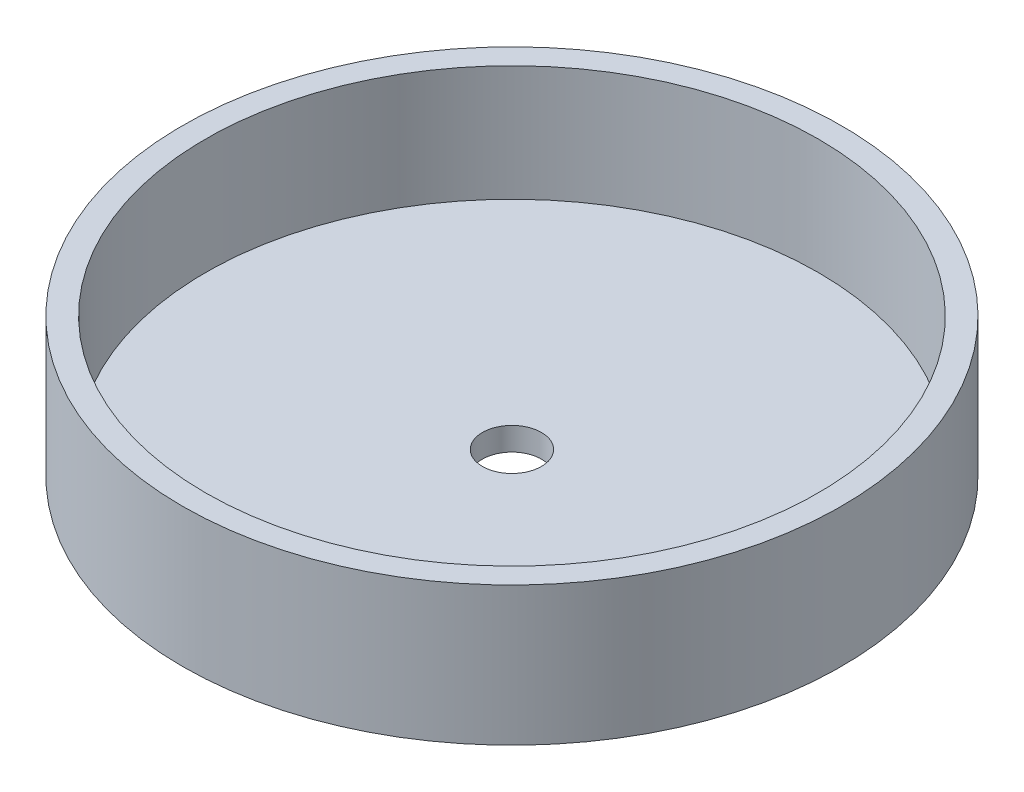
SolidWorks part; units mm, degrees
ref_plane "前视基准面" through (0, 0, 0) normal (0, 0, 1) x (1, 0, 0)
ref_plane "上视基准面" through (0, 0, 0) normal (0, 1, 0) x (1, 0, 0)
ref_plane "右视基准面" through (0, 0, 0) normal (1, 0, 0) x (0, 0, -1)
sketch "草图1" plane through (0, 0, 0) normal (0, 0, 1) x (1, 0, 0)
  line L0 (0, 9.9462) -> (0, -6.3172) construction
  line L1 (0, -3) -> (2.55, -3) construction
  line L2 (8.5753, 0) -> (-12.3118, 0) construction
  line L3 (2.55, -3) -> (2.55, 0) construction
  line L4 (2.55, 0) -> (26.5, 0)
  line L5 (26.5, 0) -> (26.5, 10)
  line L6 (26.5, 10) -> (0, 10) construction
  line L8 (0, -5) -> (4.55, -5) construction
  line L9 (4.55, -5) -> (4.55, -2) construction
  line L10 (4.55, -2) -> (28.5, -2)
  line L11 (28.5, -2) -> (28.5, 12) construction
  line L12 (28.5, 12) -> (0, 12) construction
  line L13 (2.55, -3) -> (2.55, -5) construction
  line L14 (2.55, -5) -> (4.55, -5) construction
  line L15 (26.5, 10) -> (28.5, 10)
  line L16 (28.5, 10) -> (28.5, -2)
  line L17 (4.55, -2) -> (2.55, -2)
  line L18 (2.55, 0) -> (2.55, -2)
  point P18 (2.55, -1.9699)
  dimension "D1" = 2.55
  dimension "D2" = 3
  dimension "D3" = 26.5
  dimension "D4" = 10
  dimension "D5" = 2
revolve "旋转1" add sketch "草图1" angle 360 about L0
